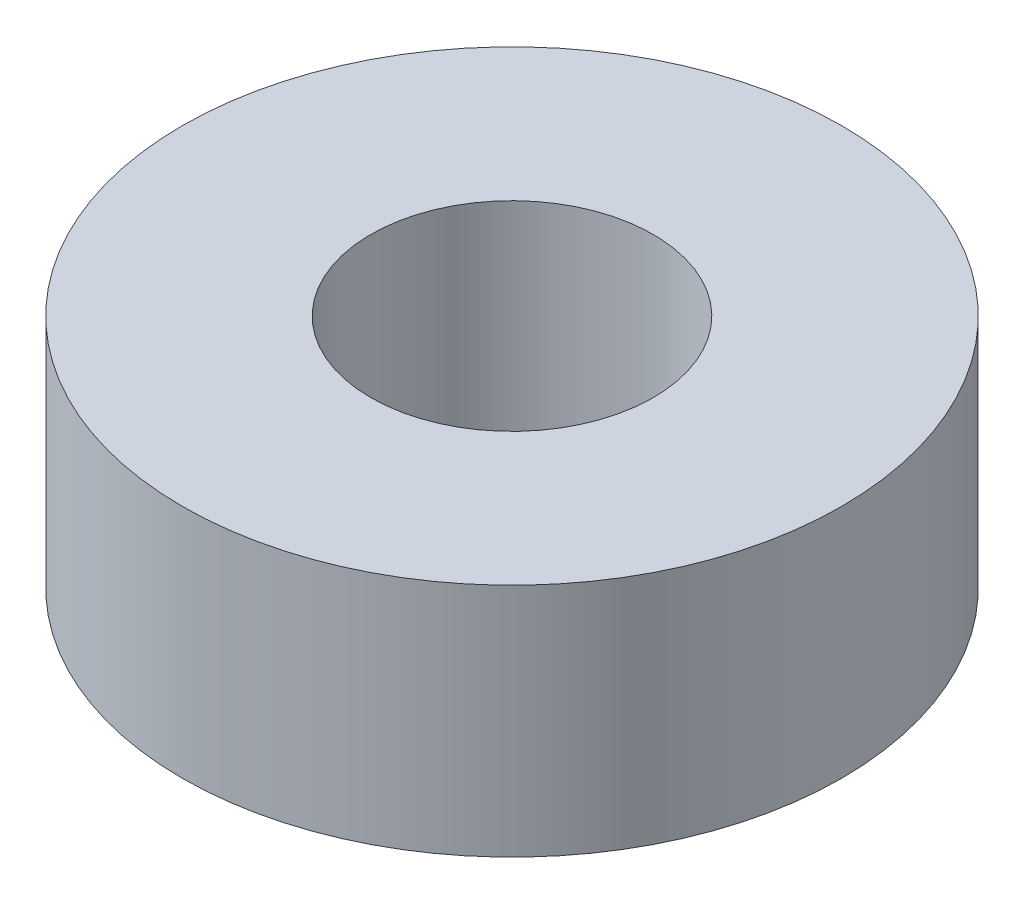
SolidWorks part; units mm, degrees
ref_plane "前视基准面" through (0, 0, 0) normal (0, 0, 1) x (1, 0, 0)
ref_plane "上视基准面" through (0, 0, 0) normal (0, 1, 0) x (1, 0, 0)
ref_plane "右视基准面" through (0, 0, 0) normal (1, 0, 0) x (0, 0, -1)
other "Configuration Table"
sketch "草图1" plane through (0, 0, 0) normal (0, 1, 0) x (1, 0, 0)
  circle A0 centre (0, 0) radius 7
  circle A1 centre (0, 0) radius 3
  dimension "D1" = 14
  dimension "D2" = 6
extrude "凸台-拉伸1" add sketch "草图1" along normal blind 5
